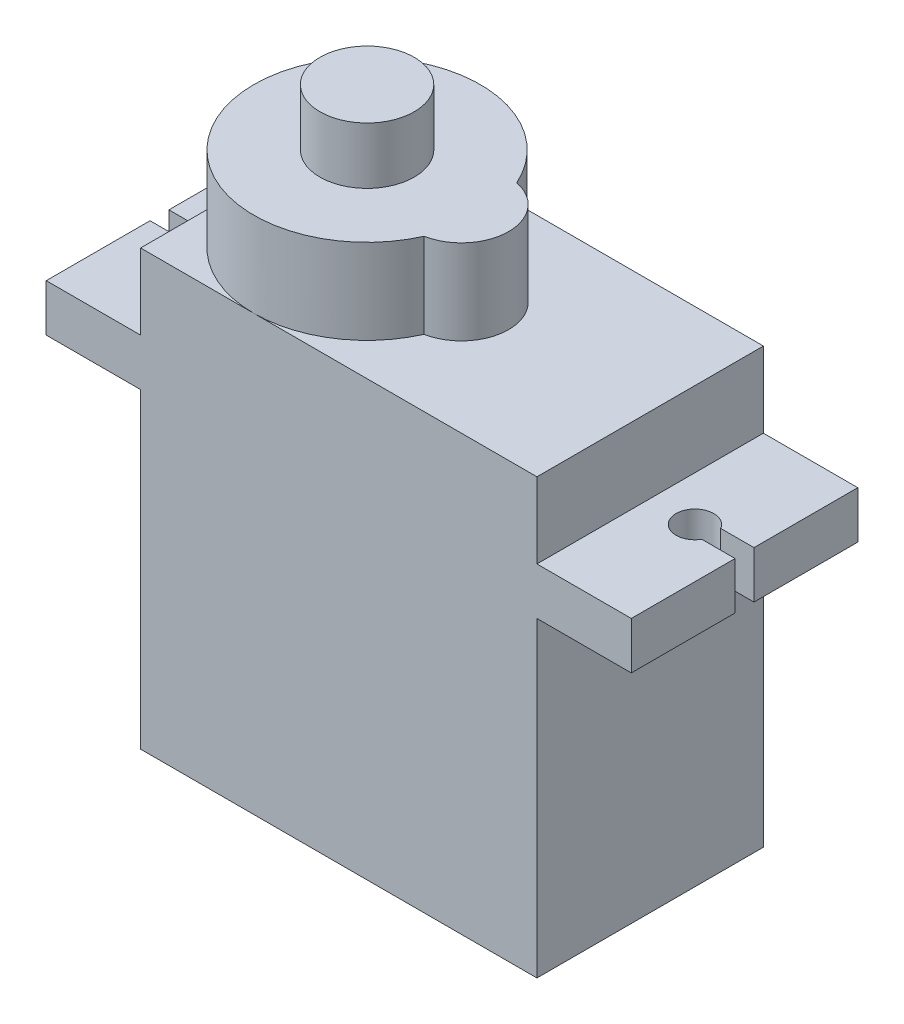
SolidWorks part; units mm, degrees
ref_plane "Front Plane" through (0, 0, 0) normal (0, 0, 1) x (1, 0, 0)
ref_plane "Top Plane" through (0, 0, 0) normal (0, 1, 0) x (1, 0, 0)
ref_plane "Right Plane" through (0, 0, 0) normal (1, 0, 0) x (0, 0, -1)
sketch "Sketch1" plane through (0, 0, 0) normal (0, 1, 0) x (1, 0, 0)
  line L1 (-10.5, -6) -> (10.5, -6)
  line L2 (-10.5, -6) -> (-10.5, 6)
  line L3 (-10.5, 6) -> (10.5, 6)
  line L4 (10.5, -6) -> (10.5, 6)
  line L5 (-10.5, -6) -> (10.5, 6) construction
  line L6 (-10.5, 6) -> (10.5, -6) construction
  point P0 (0, 0)
  dimension "D1" = 21
  dimension "D2" = 12
extrude "Boss-Extrude1" add sketch "Sketch1" along normal blind 23
sketch "Sketch2" plane through (0, 0, 6) normal (0, 0, 1) x (1, 0, 0)
  line L0 (10.5, 23) -> (10.5, 0) construction
  line L1 (10.5, 19) -> (15.5, 19)
  line L2 (10.5, 19) -> (10.5, 16.5)
  line L3 (10.5, 16.5) -> (15.5, 16.5)
  line L4 (15.5, 19) -> (15.5, 16.5)
  line L5 (0, 23) -> (0, 22.039) construction
  line L6 (-10.5, 23) -> (10.5, 23) construction
  line L7 (0, 0) -> (0, 23) construction
  line L8 (-10.5, 16.5) -> (-15.5, 16.5)
  line L9 (-15.5, 19) -> (-15.5, 16.5)
  line L10 (-10.5, 19) -> (-15.5, 19)
  line L11 (-10.5, 19) -> (-10.5, 16.5)
  dimension "D1" = 4
  dimension "D2" = 5
  dimension "D3" = 2.5
extrude "Boss-Extrude2" add sketch "Sketch2" against normal up to surface (12 mm away) up to face at (0, 11.5, -6)
sketch "Sketch3" plane through (0, 23, 0) normal (0, 1, 0) x (1, 0, 0)
  line L0 (-15.5, 0) -> (15.5, 0) construction
  line L1 (-15.5, 6) -> (-15.5, -6) construction
  line L2 (15.5, 6) -> (15.5, -6) construction
  line L3 (0, 6) -> (0, -6) construction
  line L4 (10.5, 6) -> (-10.5, 6) construction
  line L5 (-10.5, -6) -> (10.5, -6) construction
  line L6 (15.5, 0.5) -> (15.5, -0.5)
  line L7 (-15.5, 0.5) -> (-13.7374, 0.5)
  line L8 (-15.5, 0.5) -> (-15.5, -0.5)
  line L9 (-15.5, -0.5) -> (-13.7374, -0.5)
  line L11 (15.5, 0.5) -> (13.7374, 0.5)
  line L12 (15.5, -0.5) -> (13.7374, -0.5)
  arc A0 (-13.7374, -0.5) -> (-13.7374, 0.5) centre (-12.8713, 0) ccw
  arc A1 (13.7374, -0.5) -> (13.7374, 0.5) centre (12.8713, 0) cw
  dimension "D1" = 1
  dimension "D2" = 1
extrude "Cut-Extrude2" cut sketch "Sketch3" against normal blind 12 and the other way through all
sketch "Sketch4" plane through (0, 23, 0) normal (0, 1, 0) x (1, 0, 0)
  line L0 (-10.5, 0) -> (10.5, 0) construction
  line L1 (-10.5, 6) -> (-10.5, -6) construction
  line L2 (10.5, -6) -> (10.5, 6) construction
  line L3 (-10.5, 6) -> (-10.5, -6) construction
  arc A0 (0.975, 2.4545) -> (0.975, -2.4545) centre (-4.5, 0) ccw
  arc A1 (0.975, -2.4545) -> (0.975, 2.4545) centre (0.5, 0) ccw
  dimension "D1" = 12
  dimension "D3" = 5
  dimension "D2" = 5
extrude "Boss-Extrude3" add sketch "Sketch4" along normal blind 4.5
sketch "Sketch5" plane through (0, 27.5, 0) normal (0, 1, 0) x (1, 0, 0)
  circle A0 centre (-4.5, 0) radius 2.5
  dimension "D1" = 5
extrude "Boss-Extrude4" add sketch "Sketch5" along normal blind 3
